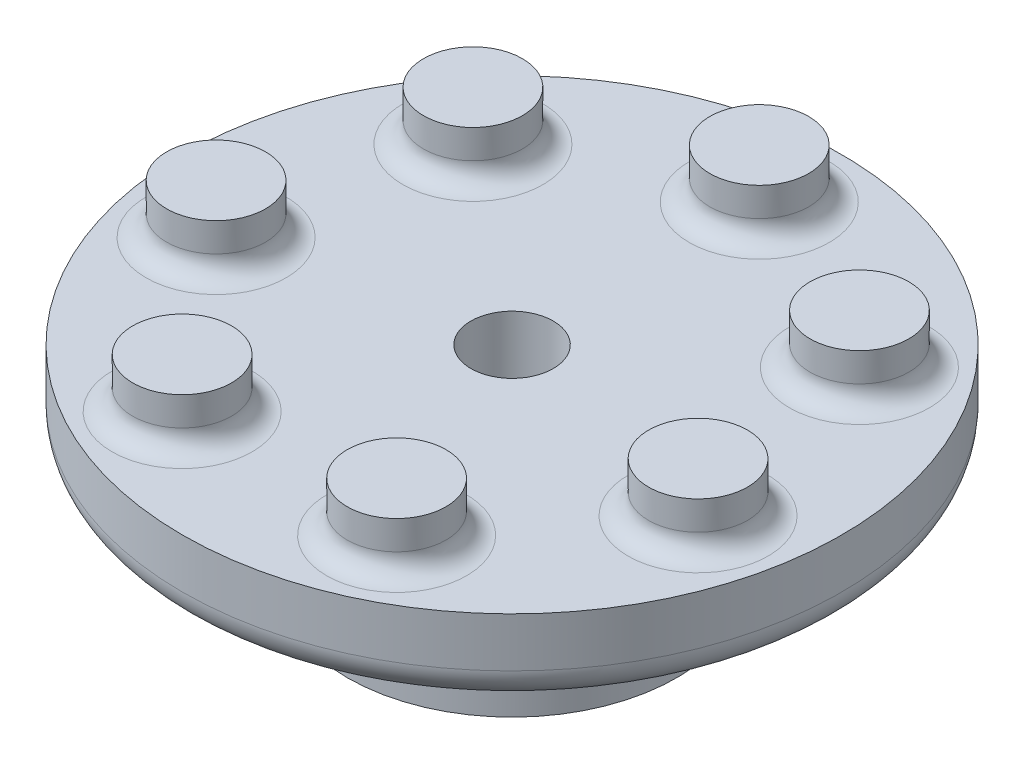
SolidWorks part; units mm, degrees
ref_plane "Front Plane" through (0, 0, 0) normal (0, 0, 1) x (1, 0, 0)
ref_plane "Top Plane" through (0, 0, 0) normal (0, 1, 0) x (1, 0, 0)
ref_plane "Right Plane" through (0, 0, 0) normal (1, 0, 0) x (0, 0, -1)
sketch "Sketch1" plane through (0, 0, 0) normal (0, 1, 0) x (1, 0, 0)
  circle A0 centre (0, 0) radius 25.4
  point P24 (0, 0)
  dimension "D1" = 50.8
extrude "Boss-Extrude1" add sketch "Sketch1" along normal blind 6.35 contours A0
sketch "Sketch2" plane through (0, 6.35, 0) normal (0, 1, 0) x (1, 0, 0)
  circle A0 centre (0, 0) radius 19.05 construction
  circle A3 centre (0, 19.05) radius 3.81
  circle A18 centre (0, 0) radius 25.4 construction
  point P24 (0, 0)
  dimension "D2" = 7.62
  dimension "D3" = 38.1
sketch "Sketch4" plane through (0, 0, 0) normal (0, -1, 0) x (1, 0, 0)
  circle A0 centre (0, 0) radius 3.175
  circle A1 centre (0, 0) radius 15.875
  dimension "D1" = 6.35
  dimension "D2" = 12.7
extrude "Cut-Extrude2" cut sketch "Sketch4" against normal up to surface (6.35 mm away) contours A0 up to face at (0, 6.35, 25.4)
extrude "Boss-Extrude3" add sketch "Sketch2" along normal blind 3.81 contours A3
fillet "Fillet2" radius 1.5875 1 edges at (0, 6.35, -15.24)
pattern_circular "CirPattern1" count 7 over 360 about axis through (0, 0, 0) along (0, 1, 0) of "Boss-Extrude3", "Fillet2"
fillet "Fillet1" radius 2.54 1 edges at (0, 0, 25.4)
scale "Scale1" scale about centroid uniform scaling yes scale factor 2
scale "Scale2" scale about centroid uniform scaling yes scale factor 2
scale "Scale3" scale about centroid uniform scaling yes scale factor 0.5
scale "Scale4" scale about centroid uniform scaling yes scale factor 0.5
sketch "Sketch5" plane through (0, 0, 0) normal (0, -1, 0) x (1, 0, 0)
  circle A0 centre (0, 0) radius 3.175
  circle A1 centre (0, 0) radius 12.7
  circle M2 centre (0, 0) radius 3.175
  dimension "D1" = 25.4
extrude "Boss-Extrude4" add sketch "Sketch5" along normal blind 9.525 contours A1 M2
sketch "Sketch6" plane through (0, -9.525, 0) normal (0, -1, 0) x (1, 0, 0)
  circle A0 centre (0, 0) radius 7.9375 construction
  circle A1 centre (-2.292, -7.5994) radius 2.159
  dimension "D1" = 15.875
  dimension "D2" = 4.318
extrude "Cut-Extrude3" cut sketch "Sketch6" against normal blind 6.35 contours A1
pattern_circular "CirPattern2" count 4 over 360 about axis through (0, 0, 0) along (0, 1, 0) of "Cut-Extrude3"
